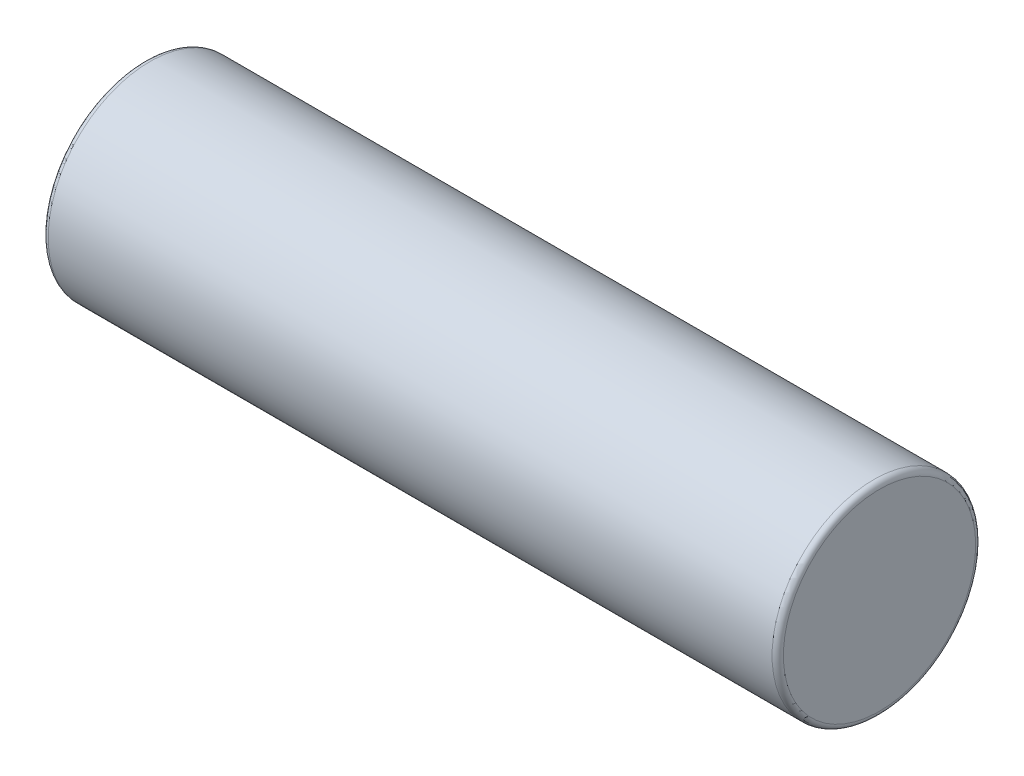
SolidWorks part; units mm, degrees
ref_plane "Спереди" through (0, 0, 0) normal (0, 0, 1) x (1, 0, 0)
ref_plane "Сверху" through (0, 0, 0) normal (0, 1, 0) x (1, 0, 0)
ref_plane "Справа" through (0, 0, 0) normal (1, 0, 0) x (0, 0, -1)
sketch "Эскиз1" plane through (0, 0, 0) normal (1, 0, 0) x (0, 0, -1)
  circle A0 centre (0, 0) radius 9
  dimension "D1" = 18
extrude "Бобышка-Вытянуть1" add sketch "Эскиз1" along normal blind 65
fillet "Скругление1" radius 0.5 2 edges at (0, 0, -9) (65, 0, -9)
